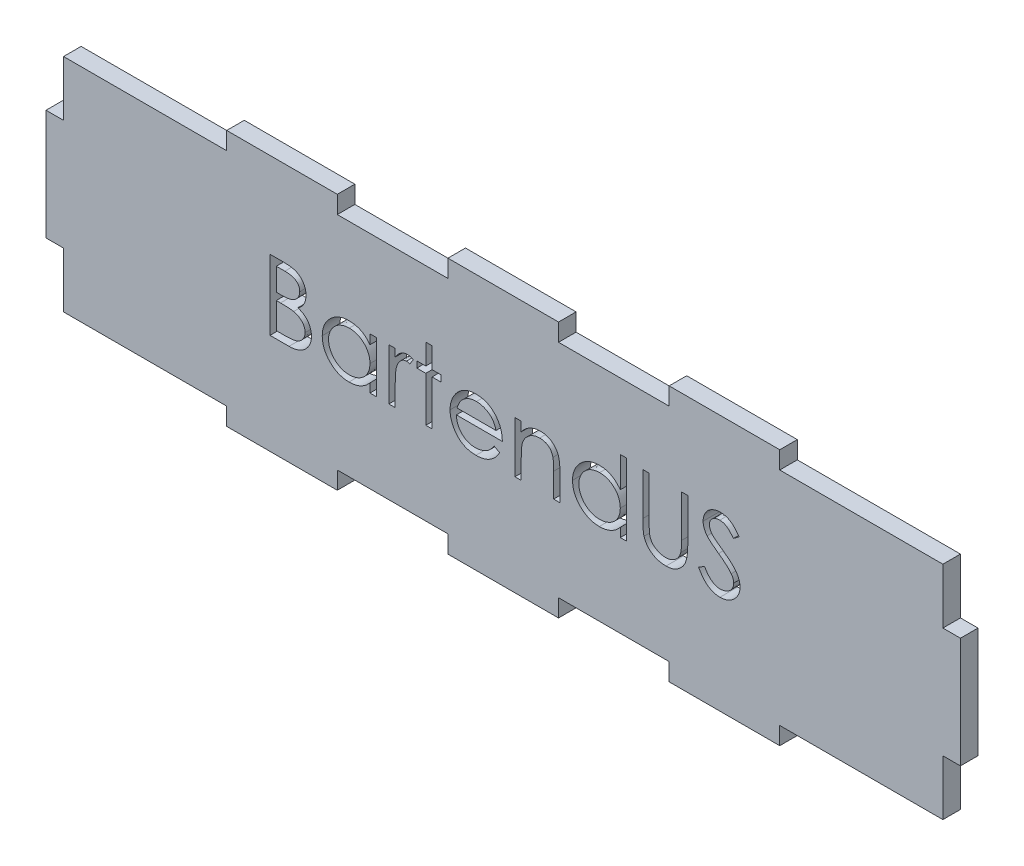
SolidWorks part; units mm, degrees
ref_plane "Plan de face" through (0, 0, 0) normal (0, 0, 1) x (1, 0, 0)
ref_plane "Plan de dessus" through (0, 0, 0) normal (0, 1, 0) x (1, 0, 0)
ref_plane "Plan de droite" through (0, 0, 0) normal (1, 0, 0) x (0, 0, -1)
sketch "Esquisse1" plane through (0, 0, 0) normal (0, 0, 1) x (1, 0, 0)
  line L1 (-82.675, 23.175) -> (82.675, 23.175)
  line L2 (-82.675, 23.175) -> (-82.675, -23.175)
  line L3 (-82.675, -23.175) -> (82.675, -23.175)
  line L4 (82.675, 23.175) -> (82.675, -23.175)
  point P4 (0, -23.175)
  point P6 (82.675, 0)
  dimension "D1" = 165.35
  dimension "D2" = 46.35
extrude "Boss.-Extru.1" add sketch "Esquisse1" along normal blind 3.175
sketch "Esquisse2" plane through (0, 0, 3.175) normal (0, 0, 1) x (1, 0, 0)
  line L0 (-82.675, 23.175) -> (-82.675, -23.175) construction
  line L11 (-82.675, 10) -> (-79.5, 10)
  line L12 (-82.675, 10) -> (-82.675, -10)
  line L13 (-82.675, -10) -> (-79.5, -10)
  line L14 (-79.5, 10) -> (-79.5, -10)
  point P6 (-79.5, 0)
  dimension "D3" = 20
  dimension "D4" = 3.175
sketch "Esquisse3" plane through (0, 0, 3.175) normal (0, 0, 1) x (1, 0, 0)
  line L16 (-82.675, -10) -> (-79.5, -10) construction
  line L17 (-82.675, -10) -> (-79.5, -10)
  line L18 (-82.675, -10) -> (-82.675, -23.175)
  line L19 (-82.675, -23.175) -> (-79.5, -23.175)
  line L20 (-79.5, -10) -> (-79.5, -23.175)
  line L21 (-82.675, -23.175) -> (82.675, -23.175) construction
  line L22 (-82.675, 23.175) -> (-82.675, -23.175) construction
  line L23 (-79.5, 10) -> (-79.5, -10) construction
  line L25 (-82.675, 23.175) -> (-79.5, 23.175)
  line L26 (-82.675, 23.175) -> (-82.675, 10)
  line L27 (-82.675, 10) -> (-79.5, 10)
  line L28 (-79.5, 23.175) -> (-79.5, 10)
extrude "Enlèv. mat.-Extru.1" cut sketch "Esquisse3" against normal through all
mirror "Symétrie1" about plane through (0, 0, 0) normal (1, 0, 0) of "Enlèv. mat.-Extru.1"
sketch "Esquisse4" plane through (0, 0, 3.175) normal (0, 0, 1) x (1, 0, 0)
  line L0 (-79.5, -23.175) -> (79.5, -23.175) construction
  line L1 (-50, -23.175) -> (-30, -23.175)
  line L2 (-50, -23.175) -> (-50, -20)
  line L3 (-50, -20) -> (-30, -20)
  line L4 (-30, -23.175) -> (-30, -20)
  line L6 (-10, -23.175) -> (10, -23.175)
  line L7 (-10, -23.175) -> (-10, -20)
  line L8 (-10, -20) -> (10, -20)
  line L9 (10, -23.175) -> (10, -20)
  line L10 (30, -23.175) -> (50, -23.175)
  line L11 (30, -23.175) -> (30, -20)
  line L12 (30, -20) -> (50, -20)
  line L13 (50, -23.175) -> (50, -20)
  point P14 (0, -20)
  dimension "D1" = 3.175
  dimension "D2" = 20
  dimension "D3" = 20
  dimension "D4" = 20
sketch "Esquisse5" plane through (0, 0, 3.175) normal (0, 0, 1) x (1, 0, 0)
  line L0 (79.5, -23.175) -> (79.5, -10) construction
  line L1 (-30, -23.175) -> (-10, -23.175)
  line L2 (-30, -23.175) -> (-30, -20)
  line L3 (-30, -20) -> (-10, -20)
  line L4 (-10, -23.175) -> (-10, -20)
  line L5 (10, -23.175) -> (30, -23.175)
  line L6 (10, -23.175) -> (10, -20)
  line L7 (10, -20) -> (30, -20)
  line L8 (30, -23.175) -> (30, -20)
  line L9 (50, -23.175) -> (79.5, -23.175)
  line L10 (50, -23.175) -> (50, -20)
  line L11 (50, -20) -> (79.5, -20)
  line L12 (79.5, -23.175) -> (79.5, -20)
  line L13 (-79.5, -23.175) -> (-79.5, -10) construction
  line L14 (-50, -23.175) -> (-79.5, -23.175)
  line L15 (-50, -23.175) -> (-50, -20)
  line L16 (-50, -20) -> (-79.5, -20)
  line L17 (-79.5, -23.175) -> (-79.5, -20)
  line L18 (-50, -20) -> (-30, -20) construction
  line L19 (30, -20) -> (50, -20) construction
extrude "Enlèv. mat.-Extru.2" cut sketch "Esquisse5" against normal through all
mirror "Symétrie2" about plane through (0, 0, 0) normal (0, 1, 0) of "Enlèv. mat.-Extru.2"
sketch "Esquisse7" plane through (0, 0, 3.175) normal (0, 0, 1) x (1, 0, 0)
  line L0 (-50, -5) -> (50, -5)
  dimension "D1" = 100
  dimension "D2" = 5
sketch "Esquisse9" plane through (0, 0, 3.175) normal (0, 0, 1) x (1, 0, 0)
  text T0 "BartendUS" font "Century Gothic" height in points 48
extrude "Enlèv. mat.-Extru.3" cut sketch "Esquisse9" against normal through all
